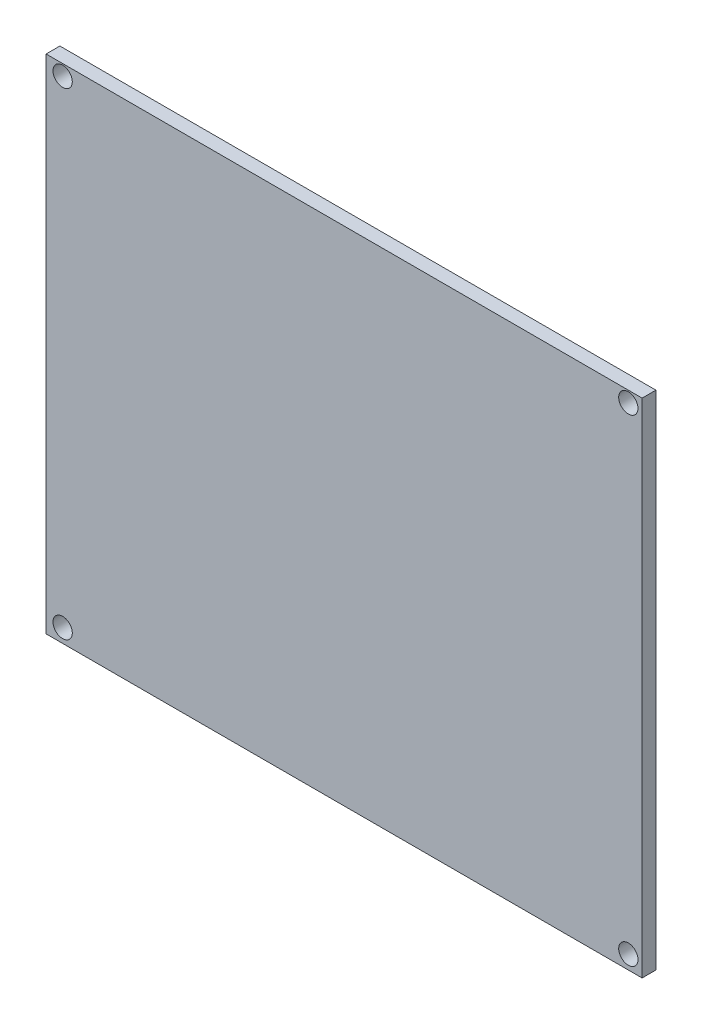
SolidWorks part; units mm, degrees
ref_plane "Plan de face" through (0, 0, 0) normal (0, 0, 1) x (1, 0, 0)
ref_plane "Plan de dessus" through (0, 0, 0) normal (0, 1, 0) x (1, 0, 0)
ref_plane "Plan de droite" through (0, 0, 0) normal (1, 0, 0) x (0, 0, -1)
sketch "Esquisse1" plane through (0, 0, 0) normal (0, 0, 1) x (1, 0, 0)
  line L1 (-10.8173, -26.149) -> (205.1827, -26.149)
  line L2 (-10.8173, -26.149) -> (-10.8173, -208.149)
  line L3 (-10.8173, -208.149) -> (205.1827, -208.149)
  line L4 (205.1827, -26.149) -> (205.1827, -208.149)
  dimension "D1" = 216
  dimension "D2" = 182
extrude "Boss.-Extru.2" add sketch "Esquisse1" along normal blind 5 contours L1 L4 L3 L2
sketch "Esquisse2" plane through (0, 0, 5) normal (0, 0, 1) x (1, 0, 0)
  line L0 (-10.8173, -208.149) -> (205.1827, -208.149) construction
  line L1 (205.1827, -26.149) -> (205.1827, -208.149) construction
  circle A0 centre (200.1827, -203.149) radius 3.5
  circle A1 centre (-4.8173, -203.149) radius 3.5
  circle A2 centre (-4.8173, -30.149) radius 3.5
  circle A3 centre (200.1827, -30.149) radius 3.5
  dimension "D1" = 5
  dimension "D5" = 173
  dimension "D2" = 5
  dimension "D3" = 2
  dimension "D4" = 2
extrude "Enlèv. mat.-Extru.1" cut sketch "Esquisse2" against normal through all
